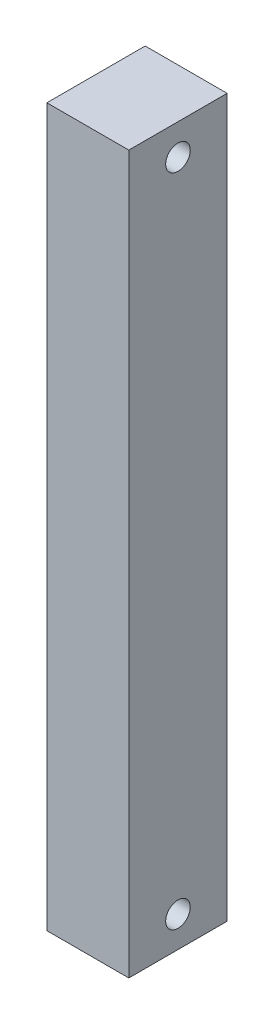
SolidWorks part; units mm, degrees
ref_plane "Front Plane" through (0, 0, 0) normal (0, 0, 1) x (1, 0, 0)
ref_plane "Top Plane" through (0, 0, 0) normal (0, 1, 0) x (1, 0, 0)
ref_plane "Right Plane" through (0, 0, 0) normal (1, 0, 0) x (0, 0, -1)
sketch "Sketch1" plane through (0, 0, 0) normal (1, 0, 0) x (0, 0, -1)
  line L0 (0, 0) -> (0, 80) construction
  line L6 (6, -3.75) -> (-6, -3.75)
  line L7 (6, -3.75) -> (6, 83.75)
  line L8 (6, 83.75) -> (-6, 83.75)
  line L9 (-6, -3.75) -> (-6, 83.75)
  line L10 (6, -3.75) -> (-6, 83.75) construction
  line L11 (6, 83.75) -> (-6, -3.75) construction
  circle A0 centre (0, 80) radius 1.5
  circle A1 centre (0, 0) radius 1.5
  point P4 (0, 40)
  dimension "D2" = 3
  dimension "D3" = 3
  dimension "D1" = 80
  dimension "D4" = 12
  dimension "D5" = 87.5
extrude "Boss-Extrude1" add sketch "Sketch1" along normal mid plane 10
